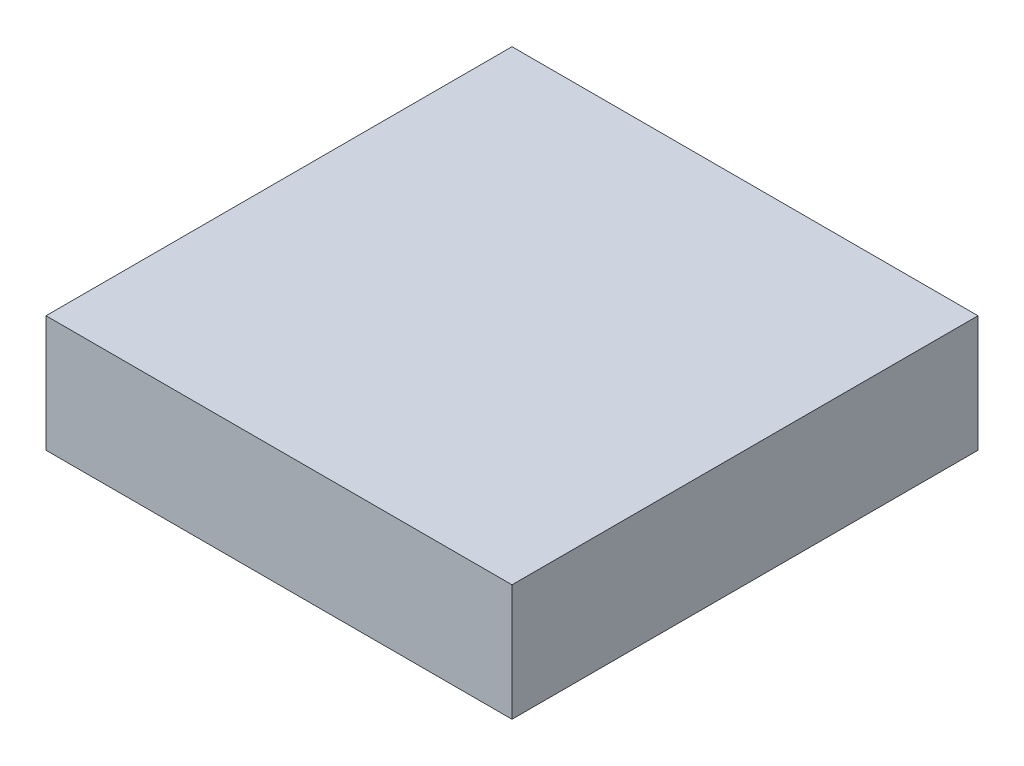
SolidWorks part; units mm, degrees
ref_plane "Front Plane" through (0, 0, 0) normal (0, 0, 1) x (1, 0, 0)
ref_plane "Top Plane" through (0, 0, 0) normal (0, 1, 0) x (1, 0, 0)
ref_plane "Right Plane" through (0, 0, 0) normal (1, 0, 0) x (0, 0, -1)
sketch "Sketch1" plane through (0, 0, 0) normal (0, 1, 0) x (1, 0, 0)
  line L1 (100, -100) -> (-100, -100)
  line L2 (100, -100) -> (100, 100)
  line L3 (100, 100) -> (-100, 100)
  line L4 (-100, -100) -> (-100, 100)
  line L5 (100, -100) -> (-100, 100) construction
  line L6 (100, 100) -> (-100, -100) construction
  point P0 (0, 0)
  dimension "D1" = 200
extrude "Boss-Extrude1" add sketch "Sketch1" along normal blind 50
